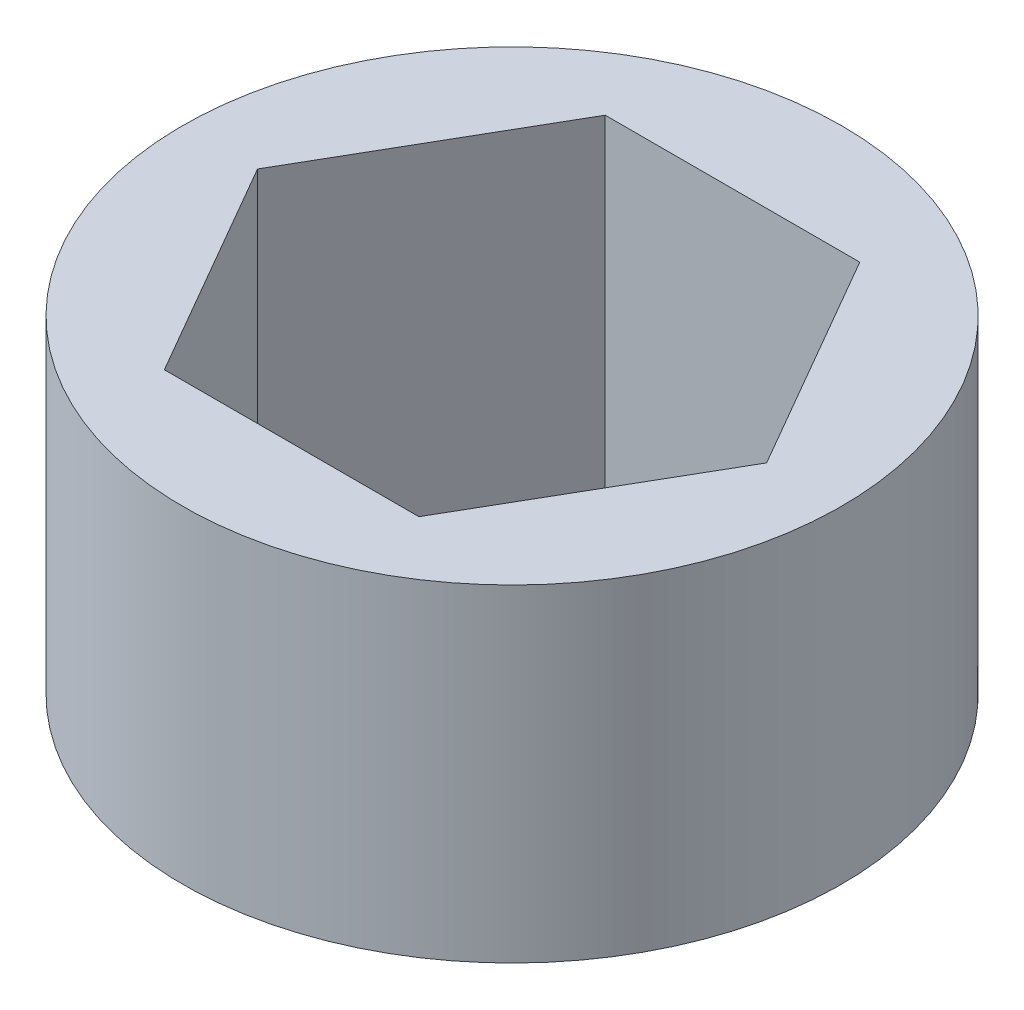
SolidWorks part; units mm, degrees
material "PET"
ref_plane "Front" through (0, 0, 0) normal (0, 0, 1) x (1, 0, 0)
ref_plane "Top" through (0, 0, 0) normal (0, 1, 0) x (1, 0, 0)
ref_plane "Right" through (0, 0, 0) normal (1, 0, 0) x (0, 0, -1)
sketch "Sketch1" plane through (0, 0, 0) normal (0, 1, 0) x (1, 0, 0)
  line L1 (3.7028, 6.4135) -> (-3.7028, 6.4135)
  line L2 (-3.7028, 6.4135) -> (-7.4057, 0)
  line L3 (-7.4057, 0) -> (-3.7028, -6.4135)
  line L4 (-3.7028, -6.4135) -> (3.7028, -6.4135)
  line L5 (3.7028, -6.4135) -> (7.4057, 0)
  line L6 (7.4057, 0) -> (3.7028, 6.4135)
  circle A0 centre (0, 0) radius 6.4135 construction
  circle A2 centre (0, 0) radius 9.5885
  point P1 (0, 6.4135)
  dimension "D2" = 3.175
  dimension "D1" = 12.827
extrude "Boss-Extrude1" add sketch "Sketch1" along normal blind 9.525
